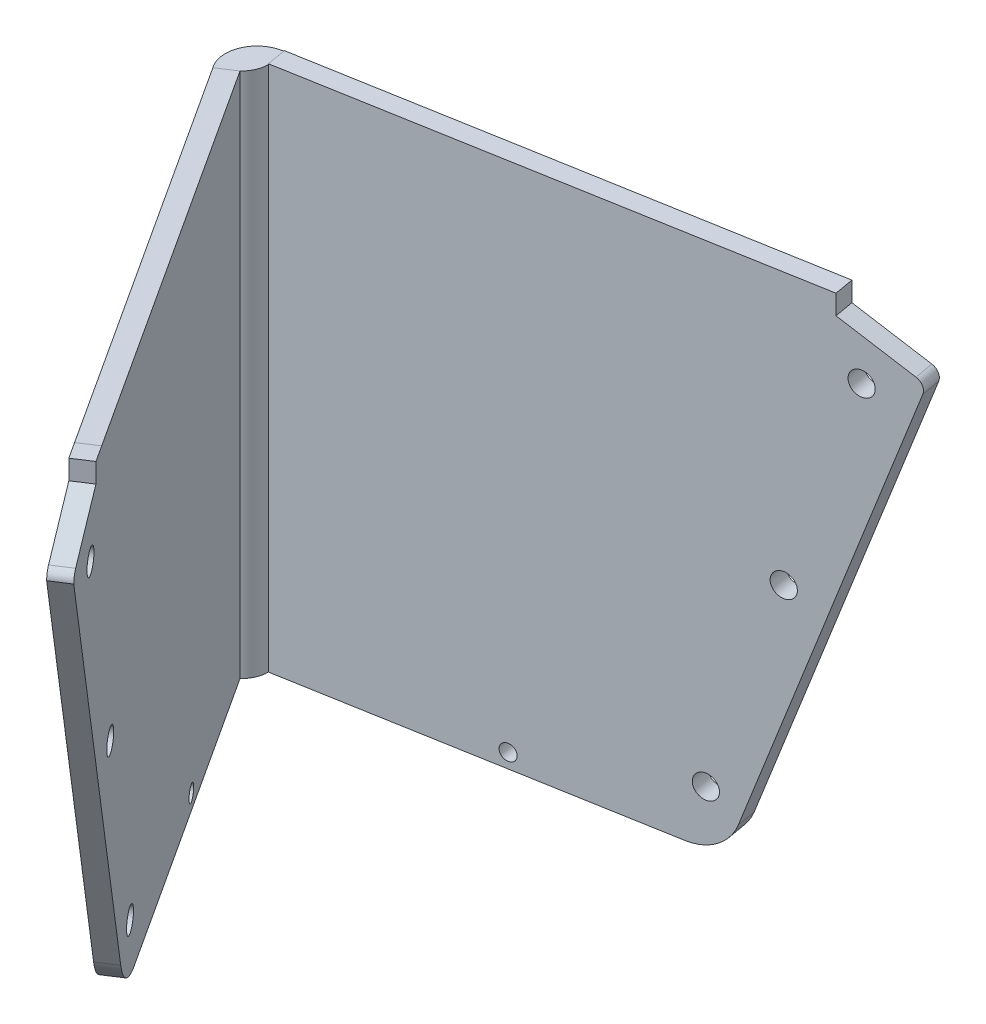
SolidWorks part; units mm, degrees
ref_plane "Front Plane" through (0, 0, 0) normal (0, 0, 1) x (1, 0, 0)
ref_plane "Top Plane" through (0, 0, 0) normal (0, 1, 0) x (1, 0, 0)
ref_plane "Right Plane" through (0, 0, 0) normal (1, 0, 0) x (0, 0, -1)
sketch "Sketch1" plane through (3.1591, 0, 17.9161) normal (-0.1736, 0, -0.9848) x (-0.9848, 0, 0.1736)
  line L0 (90.9457, -13.5582) -> (72.595, -13.5582)
  line L1 (70.2458, -11.9132) -> (62.123, 10.404) construction
  line L2 (70.2458, -11.9132) -> (62.123, 10.404)
  line L3 (62.4218, 11.0448) -> (65.9457, 12.3274)
  line L4 (65.9457, 12.3274) -> (65.9457, 13.3274)
  line L5 (65.9457, 13.3274) -> (66.9457, 13.3274)
  line L10 (90.9457, -12.0582) -> (90.9457, -13.5582)
  line L11 (90.9457, -12.0582) -> (90.9457, 13.3274)
  line L12 (66.9457, 13.3274) -> (90.9457, 13.3274)
  arc A0 (72.595, -13.5582) -> (70.2458, -11.9132) centre (72.595, -11.0582) cw
  arc A1 (70.2458, -11.9132) -> (72.595, -13.5582) centre (72.595, -11.0582) ccw construction
  arc A2 (62.123, 10.404) -> (62.4218, 11.0448) centre (62.5928, 10.575) cw
  circle A7 centre (64.816, 9.7887) radius 0.6
  circle A8 centre (68.2465, -0.5071) radius 0.6
  circle A9 centre (71.677, -10.8029) radius 0.6
  circle A10 centre (80.3897, -12.8204) radius 0.4
  line M17 (90.9457, -12.0582) -> (75.2753, -12.0582)
  line M18 (75.2753, -12.0582) -> (74.5615, -11.3443)
  line M19 (74.5615, -11.3443) -> (66.9457, 9.5799)
  line M20 (66.9457, 9.5799) -> (66.9457, 13.3274)
  line M21 (66.9457, 13.3274) -> (65.9457, 13.3274)
  line M22 (65.9457, 13.3274) -> (65.9457, 12.3274)
  line M23 (65.9457, 12.3274) -> (62.4218, 11.0448)
  arc M24 (62.4218, 11.0448) -> (62.123, 10.404) centre (62.5928, 10.575) ccw
  line M25 (62.123, 10.404) -> (70.2458, -11.9132)
  arc M26 (70.2458, -11.9132) -> (72.595, -13.5582) centre (72.595, -11.0582) ccw
  line M27 (72.595, -13.5582) -> (90.9457, -13.5582)
  line M28 (90.9457, -13.5582) -> (90.9457, -12.0582)
  circle M29 centre (71.677, -10.8029) radius 0.5
  circle M30 centre (80.3897, -12.8204) radius 0.3
  circle M31 centre (68.2465, -0.5071) radius 0.5
  circle M32 centre (64.816, 9.7887) radius 0.5
  dimension "D1" = 1.2
  dimension "D2" = 1.2
  dimension "D3" = 1.2
  dimension "D4" = 0.8
extrude "Boss-Extrude2" add sketch "Sketch1" along normal blind 1 contours L12 L11 M20 M19 M18 M17 | M28 M17 M18 M19 M20 M21 M22 M23 M24 M25 M26 M27 M30 M32 M31 M29
sketch "Sketch2" plane through (0, -13.5582, 0) normal (0, -1, 0) x (-1, 0, 0)
  line L0 (86.4049, -33.7086) -> (86.4049, -32.7086)
  line L1 (86.8451, -34.721) -> (87.5764, -35.403)
  arc A0 (86.8451, -34.721) -> (86.4049, -33.7086) centre (87.7891, -33.7086) cw
  arc A1 (86.4049, -32.7086) -> (87.5764, -35.403) centre (86.3765, -34.3229) cw
  dimension "D1" = 1
  dimension "D2" = 1
  dimension "D3" = 1
extrude "Boss-Extrude3" add sketch "Sketch2" against normal blind 26.85 separate body
sketch "Sketch3" plane through (-76.9437, 0, 49.9678) normal (-0.8387, 0, 0.5446) x (0.5446, 0, 0.8387)
  line L0 (-18.1798, -13.5582) -> (0.1709, -13.5582)
  line L1 (2.5201, -11.9132) -> (10.6731, 10.575)
  line L2 (10.3441, 11.0448) -> (6.8202, 12.3274)
  line L3 (6.8202, 12.3274) -> (6.8202, 13.3274)
  line L4 (6.8202, 13.3274) -> (5.8202, 13.3274)
  line L5 (5.8202, 13.3274) -> (-18.1798, 13.2918)
  line L6 (-18.1798, 13.2918) -> (-18.1798, -13.5582)
  arc A0 (0.1709, -13.5582) -> (2.5201, -11.9132) centre (0.1709, -11.0582) ccw
  arc A1 (10.6429, 10.404) -> (10.3441, 11.0448) centre (10.1731, 10.575) ccw construction
  arc A2 (10.3441, 11.0448) -> (10.6731, 10.575) centre (10.1731, 10.575) cw
  circle A4 centre (4.3389, -0.7249) radius 0.6
  circle A5 centre (7.7694, 9.5709) radius 0.6
  circle A6 centre (0.9084, -11.0207) radius 0.6
  circle A7 centre (-9.7379, -12.7799) radius 0.4
  circle M10 centre (-9.7379, -12.7799) radius 0.3
  circle M11 centre (0.9084, -11.0207) radius 0.5
  circle M12 centre (7.7694, 9.5709) radius 0.5
  circle M13 centre (4.3389, -0.7249) radius 0.5
  line M14 (5.8202, 9.5799) -> (-1.7956, -11.3443)
  line M15 (-1.7956, -11.3443) -> (-2.5094, -12.0582)
  line M16 (-2.5094, -12.0582) -> (-18.1798, -12.0582)
  line M17 (-18.1798, -12.0582) -> (-18.1798, -13.5582)
  line M18 (-18.1798, -13.5582) -> (0.1709, -13.5582)
  arc M19 (0.1709, -13.5582) -> (2.5201, -11.9132) centre (0.1709, -11.0582) ccw
  arc M21 (10.6429, 10.404) -> (10.3441, 11.0448) centre (10.1731, 10.575) ccw
  line M22 (10.3441, 11.0448) -> (6.8202, 12.3274)
  line M23 (6.8202, 12.3274) -> (6.8202, 13.3274)
  line M24 (6.8202, 13.3274) -> (5.8202, 13.3274)
  line M25 (5.8202, 13.3274) -> (5.8202, 9.5799)
  dimension "D1" = 1.2
  dimension "D2" = 1.2
  dimension "D3" = 1.2
  dimension "D4" = 0.8
extrude "Boss-Extrude4" add sketch "Sketch3" along normal blind 1 contours L5 L6 M16 M15 M14 M25 | L1 M19 M21 M22 M23 M24 M25 M14 M15 M16 M17 M18 M11 M13 M12 M10
